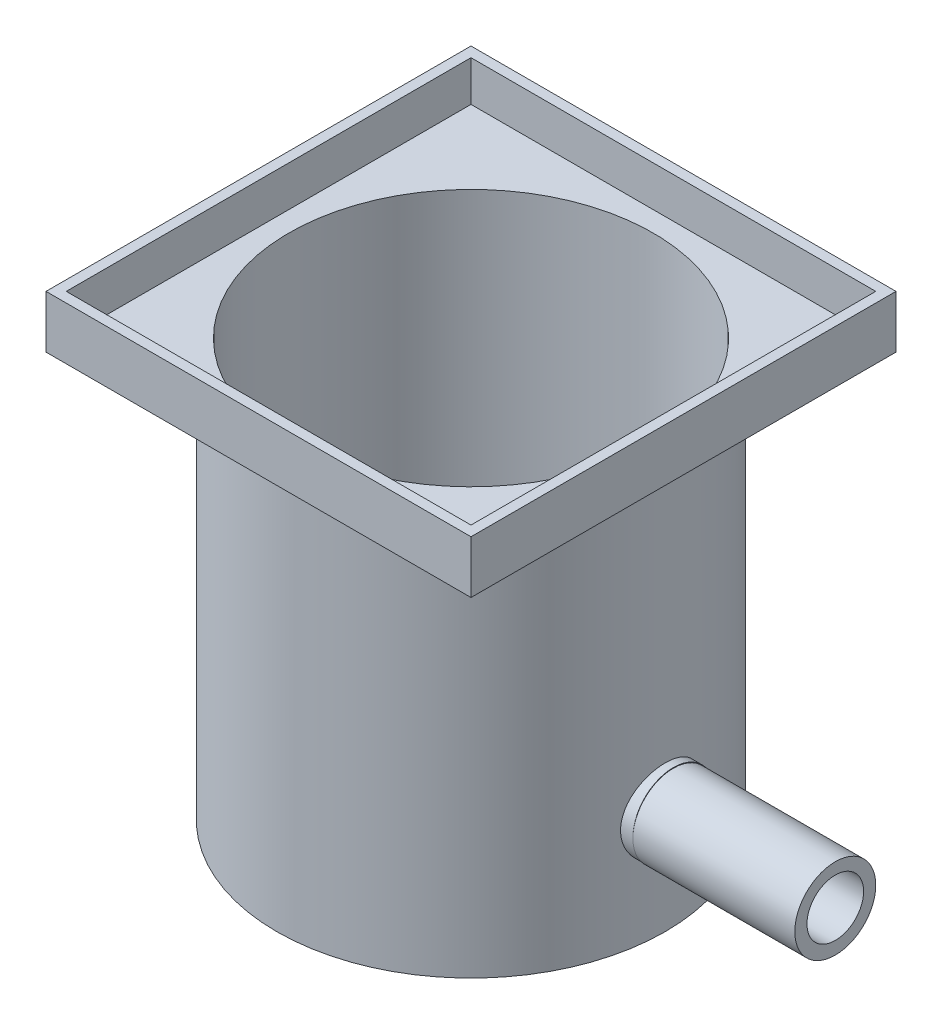
SolidWorks part; units mm, degrees
ref_plane "Front Plane" through (0, 0, 0) normal (0, 0, 1) x (1, 0, 0)
ref_plane "Top Plane" through (0, 0, 0) normal (0, 1, 0) x (1, 0, 0)
ref_plane "Right Plane" through (0, 0, 0) normal (1, 0, 0) x (0, 0, -1)
sketch "Sketch3" plane through (0, 0, 0) normal (0, 1, 0) x (1, 0, 0)
  circle A0 centre (0, 0) radius 48
  circle A1 centre (0, 0) radius 45
extrude "Boss-Extrude1" add sketch "Sketch3" along normal blind 100
ref_plane "Plane2" through (50, 0, 0) normal (1, 0, 0) x (0, 0, -1)
sketch "Sketch5" plane through (50, 0, 0) normal (1, 0, 0) x (0, 0, -1)
  circle A0 centre (0, 26.1261) radius 10
extrude "Boss-Extrude2" add sketch "Sketch5" against normal up to surface (3.0532 mm away)
sketch "Sketch6" plane through (50, 0, 0) normal (1, 0, 0) x (0, 0, -1)
  circle A0 centre (0, 25.975) radius 10
extrude "Boss-Extrude3" add sketch "Sketch6" along normal blind 40
sketch "Sketch7" plane through (90, 0, 0) normal (1, 0, 0) x (0, 0, -1)
  circle A0 centre (0, 26.1261) radius 7
extrude "Cut-Extrude1" cut sketch "Sketch7" against normal blind 55
sketch "Sketch8" plane through (0, 100, 0) normal (0, 1, 0) x (1, 0, 0)
  line L1 (-52.5, 52.5) -> (52.5, 52.5)
  line L2 (-52.5, 52.5) -> (-52.5, -52.5)
  line L3 (-52.5, -52.5) -> (52.5, -52.5)
  line L4 (52.5, 52.5) -> (52.5, -52.5)
  line L5 (-52.5, 52.5) -> (52.5, -52.5) construction
  line L6 (-52.5, -52.5) -> (52.5, 52.5) construction
  circle A0 centre (0, 0) radius 45
  point P0 (0, 0)
  dimension "D1" = 105
  dimension "D2" = 105
extrude "Boss-Extrude4" add sketch "Sketch8" along normal blind 3
sketch "Sketch9" plane through (0, 103, 0) normal (0, 1, 0) x (1, 0, 0)
  line L1 (-52.5, 52.5) -> (52.5, 52.5)
  line L2 (-52.5, 52.5) -> (-52.5, -52.5)
  line L3 (-52.5, -52.5) -> (52.5, -52.5)
  line L4 (52.5, 52.5) -> (52.5, -52.5)
  line L5 (-52.5, 52.5) -> (52.5, -52.5) construction
  line L6 (-52.5, -52.5) -> (52.5, 52.5) construction
  line L7 (-50, 50) -> (50, 50)
  line L8 (-50, 50) -> (-50, -50)
  line L9 (-50, -50) -> (50, -50)
  line L10 (50, 50) -> (50, -50)
  line L11 (-50, 50) -> (50, -50) construction
  line L12 (-50, -50) -> (50, 50) construction
  point P0 (0, 0)
  point P7 (0, 0)
  dimension "D1" = 100
  dimension "D2" = 100
extrude "Boss-Extrude5" add sketch "Sketch9" along normal blind 10
